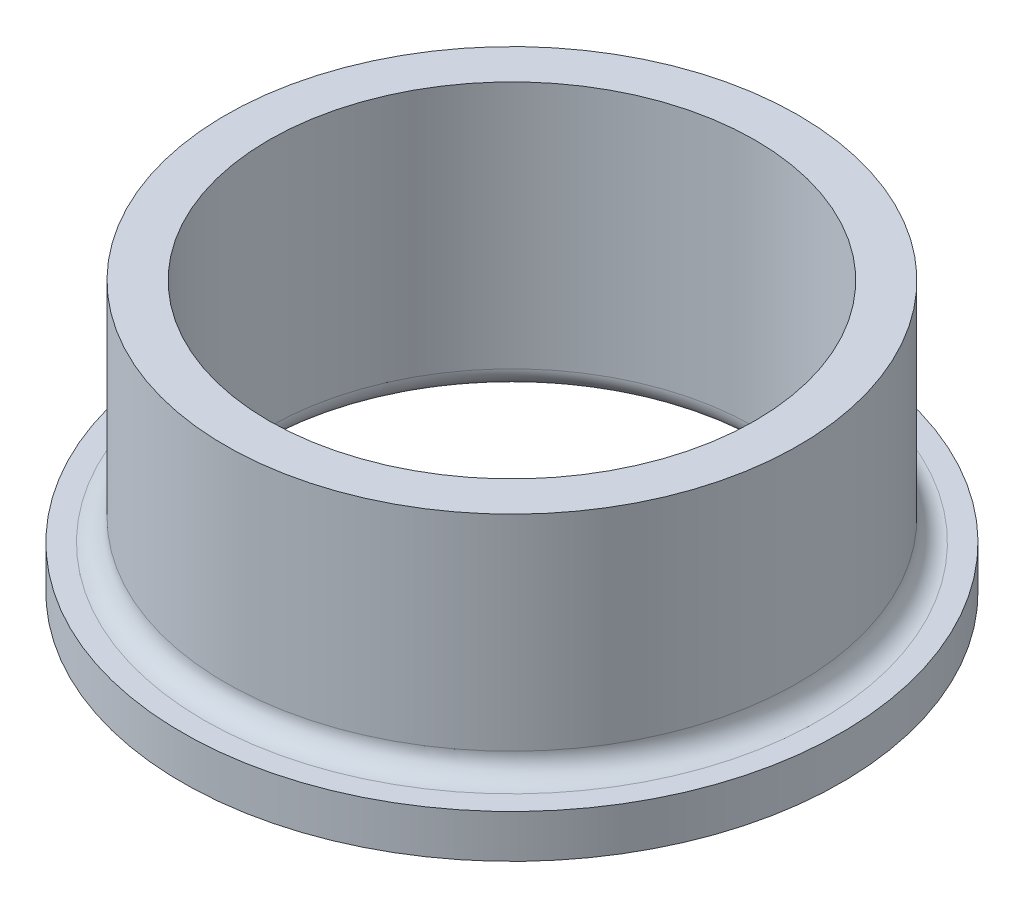
SolidWorks part; units mm, degrees
ref_plane "Front Plane" through (0, 0, 0) normal (0, 0, 1) x (1, 0, 0)
ref_plane "Top Plane" through (0, 0, 0) normal (0, 1, 0) x (1, 0, 0)
ref_plane "Right Plane" through (0, 0, 0) normal (1, 0, 0) x (0, 0, -1)
sketch "Sketch1" plane through (0, 0, 0) normal (0, 0, 1) x (1, 0, 0)
  line L0 (0, 0) -> (0, 25) construction
  line L1 (22.5, 25) -> (22.5, 2)
  line L2 (24.5, 0) -> (30.5, 0)
  line L3 (30.5, 0) -> (30.5, 4)
  line L4 (30.5, 4) -> (28.5, 4)
  line L5 (26.5, 6) -> (26.5, 25)
  line L6 (26.5, 25) -> (22.5, 25)
  arc A0 (28.5, 4) -> (26.5, 6) centre (28.5, 6) cw
  arc A1 (22.5, 2) -> (24.5, 0) centre (24.5, 2) ccw
  point P15 (22.5, 0)
  dimension "D6" = 2
  dimension "D7" = 2
  dimension "D1" = 25
  dimension "D2" = 22.5
  dimension "D3" = 8
  dimension "D4" = 4
  dimension "D5" = 4
revolve "Revolve1" add sketch "Sketch1" angle 360 about L0
